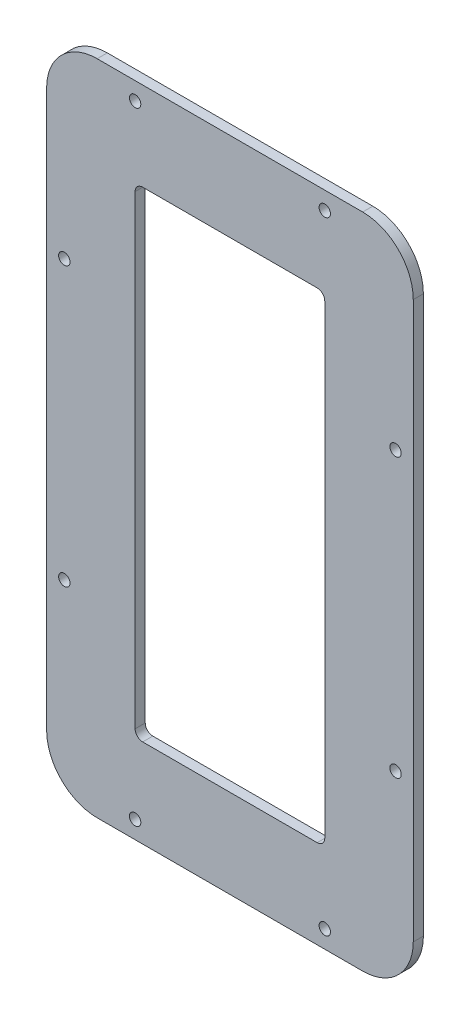
SolidWorks part; units mm, degrees
ref_plane "Plano frontal" through (0, 0, 0) normal (0, 0, 1) x (1, 0, 0)
ref_plane "Plano superior" through (0, 0, 0) normal (0, 1, 0) x (1, 0, 0)
ref_plane "Plano direito" through (0, 0, 0) normal (1, 0, 0) x (0, 0, -1)
sketch "Esboço1" plane through (0, 0, 0) normal (0, 0, 1) x (1, 0, 0)
  line L1 (-72.5, -130) -> (72.5, -130)
  line L2 (-72.5, -130) -> (-72.5, 130)
  line L3 (-72.5, 130) -> (72.5, 130)
  line L4 (72.5, -130) -> (72.5, 130)
  line L5 (-72.5, -130) -> (72.5, 130) construction
  line L6 (-72.5, 130) -> (72.5, -130) construction
  line L7 (-34.5, -95) -> (34.5, -95)
  line L8 (-37.5, -92) -> (-37.5, 92)
  line L9 (-34.5, 95) -> (34.5, 95)
  line L10 (37.5, -92) -> (37.5, 92)
  line L11 (-37.5, -95) -> (37.5, 95) construction
  line L12 (-37.5, 95) -> (37.5, -95) construction
  arc A0 (-34.5, 95) -> (-37.5, 92) centre (-34.5, 92) ccw
  arc A1 (-37.5, -92) -> (-34.5, -95) centre (-34.5, -92) ccw
  arc A2 (34.5, -95) -> (37.5, -92) centre (34.5, -92) ccw
  arc A3 (37.5, 92) -> (34.5, 95) centre (34.5, 92) ccw
  point P0 (0, 0)
  point P6 (0, 0)
  dimension "D5" = 3
  dimension "D1" = 145
  dimension "D2" = 260
  dimension "D3" = 75
  dimension "D4" = 190
extrude "Ressalto-extrusão1" add sketch "Esboço1" along normal blind 4
sketch "Esboço5" plane through (0, 0, 4) normal (0, 0, 1) x (1, 0, 0)
  line L1 (-65.5, -123) -> (65.5, -123) construction
  line L2 (-65.5, -123) -> (-65.5, 123) construction
  line L3 (-65.5, 123) -> (65.5, 123) construction
  line L4 (65.5, -123) -> (65.5, 123) construction
  line L5 (-65.5, -123) -> (65.5, 123) construction
  line L6 (-65.5, 123) -> (65.5, -123) construction
  line L8 (72.5, 130) -> (-72.5, 130) construction
  line L9 (-72.5, 130) -> (-72.5, -130) construction
  point P0 (0, 0)
  dimension "D1" = 7
  dimension "D2" = 7
hole_wizard "Furo com folga de M41" positions "Esboço7" profile "Esboço6" hole size "M4" standard "ISO" end condition up to next
sketch "Esboço7" plane through (0, 0, 4) normal (0, 0, 1) x (1, 0, 0)
  line L0 (-65.5, 123) -> (65.5, 123) construction
  line L1 (65.5, -123) -> (65.5, 123) construction
  line L2 (-65.5, -123) -> (65.5, -123) construction
  line L3 (-65.5, -123) -> (-65.5, 123) construction
  line L4 (-72.5, 130) -> (-72.5, -130) construction
  line L5 (72.5, 130) -> (-72.5, 130) construction
  line L6 (-72.5, -130) -> (72.5, -130) construction
  line L7 (72.5, -130) -> (72.5, 130) construction
  point P0 (-37.5, 123)
  point P1 (37.5, 123)
  point P5 (65.5, 55)
  point P9 (65.5, -55)
  point P11 (37.5, -123)
  point P15 (-37.5, -123)
  point P17 (-65.5, -55)
  point P21 (-65.5, 55)
  dimension "D1" = 35
  dimension "D2" = 75
  dimension "D3" = 35
  dimension "D4" = 75
  dimension "D5" = 75
  dimension "D6" = 35
  dimension "D7" = 35
  dimension "D8" = 75
sketch "Esboço6" plane through (-37.5, 123, 4) normal (1, 0, 0) x (0, -1, 0)
  line L0 (0, 0) -> (0, 4)
  line L1 (0, 4) -> (2.25, 4)
  line L2 (2.25, 4) -> (2.25, 0)
  line L5 (2.25, 0) -> (0, 0)
  line L11 (0, -6.35) -> (0, 107.95) construction
  dimension "Thru Hole Dia." = 4.5
  dimension "Thru Hole Depth" = 4
fillet "Filete1" radius 20 4 edges at (72.5, -130, 2) (-72.5, -130, 2) (72.5, 130, 2) (-72.5, 130, 2)
